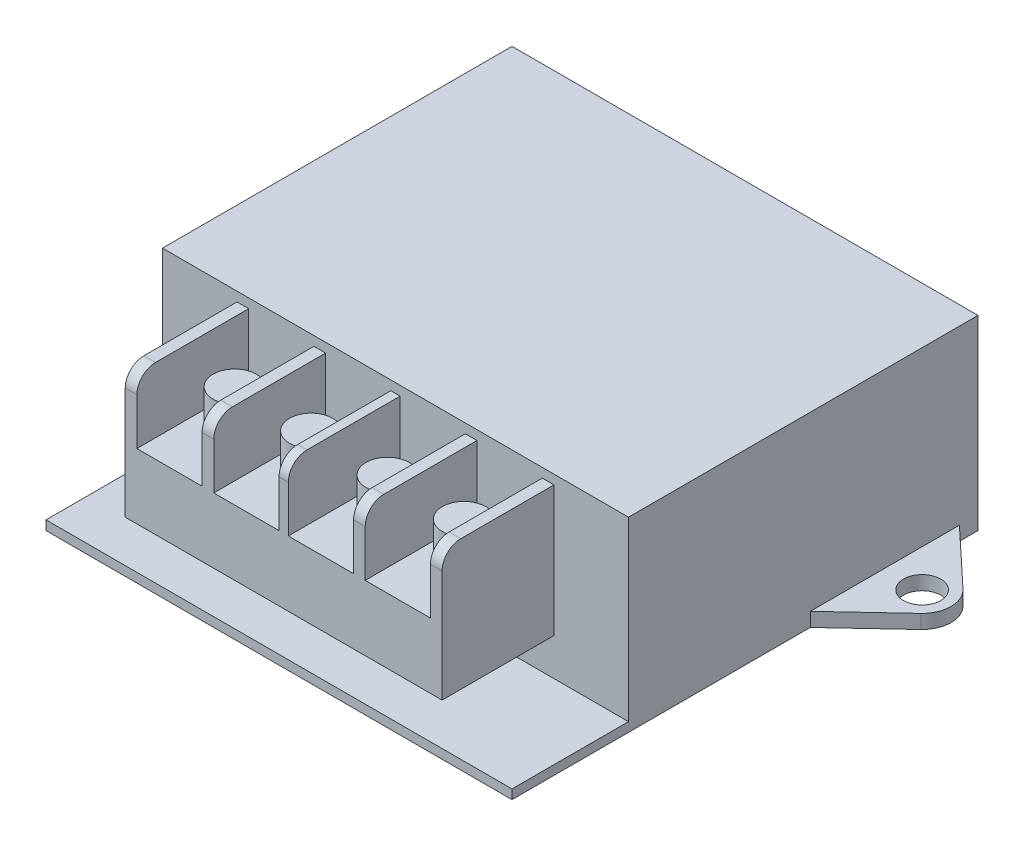
SolidWorks part; units mm, degrees
ref_plane "Front Plane" through (0, 0, 0) normal (0, 0, 1) x (1, 0, 0)
ref_plane "Top Plane" through (0, 0, 0) normal (0, 1, 0) x (1, 0, 0)
ref_plane "Right Plane" through (0, 0, 0) normal (1, 0, 0) x (0, 0, -1)
sketch "Sketch1" plane through (0, 0, 0) normal (0, 1, 0) x (1, 0, 0)
  line L1 (0, 0) -> (50, 0)
  line L2 (0, 0) -> (0, 50)
  line L3 (0, 50) -> (50, 50)
  line L4 (50, 0) -> (50, 50)
  dimension "D1" = 50
  dimension "D2" = 50
extrude "Boss-Extrude1" add sketch "Sketch1" along normal blind 1
sketch "Sketch2" plane through (0, 1, 0) normal (0, 1, 0) x (1, 0, 0)
  line L0 (50, 0) -> (50, 50) construction
  line L1 (0, 50) -> (50, 50)
  line L2 (0, 50) -> (0, 12.5)
  line L3 (0, 12.5) -> (50, 12.5)
  line L4 (50, 50) -> (50, 12.5)
  dimension "D1" = 37.5
extrude "Boss-Extrude2" add sketch "Sketch2" along normal blind 19
sketch "Sketch3" plane through (0, 0, -12.5) normal (0, 0, 1) x (1, 0, 0)
  line L0 (0, 20) -> (50, 20) construction
  line L1 (8, 19) -> (42, 19)
  line L2 (8, 19) -> (8, 5)
  line L3 (8, 5) -> (42, 5)
  line L4 (42, 19) -> (42, 5)
  point P4 (25, 20)
  point P5 (25, 19)
  point P6 (0, 0)
  dimension "D1" = 34
  dimension "D2" = 14
  dimension "D3" = 1
extrude "Boss-Extrude3" add sketch "Sketch3" along normal blind 12
sketch "Sketch4" plane through (0, 0, 0) normal (0, -1, 0) x (1, 0, 0)
  line L0 (0, -50) -> (0, 0) construction
  line L2 (-6.1215, -37.7396) -> (0, -32.0038)
  line L3 (-6.1215, -42.2679) -> (0, -48.0038)
  circle A0 centre (-4, -40.0038) radius 2
  arc A2 (-6.1215, -37.7396) -> (-6.1215, -42.2679) centre (-4, -40.0038) ccw
  point P4 (-7, -40.7957)
  line M6 (0, 0) -> (0, -50)
  dimension "D1" = 4
  dimension "D2" = 4
  dimension "D3" = 16
  dimension "D4" = 7
extrude "Boss-Extrude4" add sketch "Sketch4" against normal blind 1.5 contours L2 A2 L3 A0 M6
ref_plane "Plane1" through (25, 0, 0) normal (-1, 0, 0) x (0, 0, 1)
mirror "Mirror1" about plane through (25, 0, 0) normal (-1, 0, 0) of "Boss-Extrude4"
sketch "Sketch5" plane through (0, 19, 0) normal (0, 1, 0) x (1, 0, 0)
  line L0 (42, 0.5) -> (8, 0.5) construction
  line L1 (9.25, 0.5) -> (16.25, 0.5)
  line L2 (9.25, 0.5) -> (9.25, 12.5)
  line L3 (9.25, 12.5) -> (16.25, 12.5)
  line L4 (16.25, 0.5) -> (16.25, 12.5)
  line L5 (8, 0.5) -> (8, 12.5) construction
  line L6 (17.5, 0.5) -> (24.5, 0.5)
  line L7 (17.5, 0.5) -> (17.5, 12.5)
  line L8 (17.5, 12.5) -> (24.5, 12.5)
  line L9 (24.5, 0.5) -> (24.5, 12.5)
  line L10 (25.5, 0.5) -> (32.5, 0.5)
  line L11 (25.5, 0.5) -> (25.5, 12.5)
  line L12 (25.5, 12.5) -> (32.5, 12.5)
  line L13 (32.5, 0.5) -> (32.5, 12.5)
  line L14 (33.75, 0.5) -> (40.75, 0.5)
  line L15 (33.75, 0.5) -> (33.75, 12.5)
  line L16 (33.75, 12.5) -> (40.75, 12.5)
  line L17 (40.75, 0.5) -> (40.75, 12.5)
  line L18 (42, 0.5) -> (42, 12.5) construction
  line L19 (0, 12.5) -> (50, 12.5) construction
  line M16 (42, 12.5) -> (8, 12.5)
  line M18 (8, 0.5) -> (42, 0.5)
  dimension "D1" = 7
  dimension "D2" = 1.25
  dimension "D3" = 1.25
  dimension "D4" = 1.25
  dimension "D5" = 1.25
extrude "Cut-Extrude1" cut sketch "Sketch5" against normal blind 7 contours L9 L7 M18 M16 | L13 L11 M18 M16 | L17 L15 M18 M16 | L1 L4 L3 L2
fillet "Fillet1" radius 2 5 edges at (41.375, 19, -0.5) (33.125, 19, -0.5) (25, 19, -0.5) (16.875, 19, -0.5) (8.625, 19, -0.5)
sketch "Sketch6" plane through (0, 12, 0) normal (0, 1, 0) x (1, 0, 0)
  line L0 (9.25, 0.5) -> (16.25, 0.5) construction
  line L1 (9.25, 2.5) -> (9.25, 12.5) construction
  circle A0 centre (12.75, 7.5) radius 2.3214
  point P2 (12.75, 0.5)
  point P3 (0, 0)
  point P6 (9.25, 7.5)
extrude "Boss-Extrude5" add sketch "Sketch6" along normal blind 4
pattern_linear "LPattern1" count 4 spacing 8.2 along (1, 0, 0) of "Boss-Extrude5"
